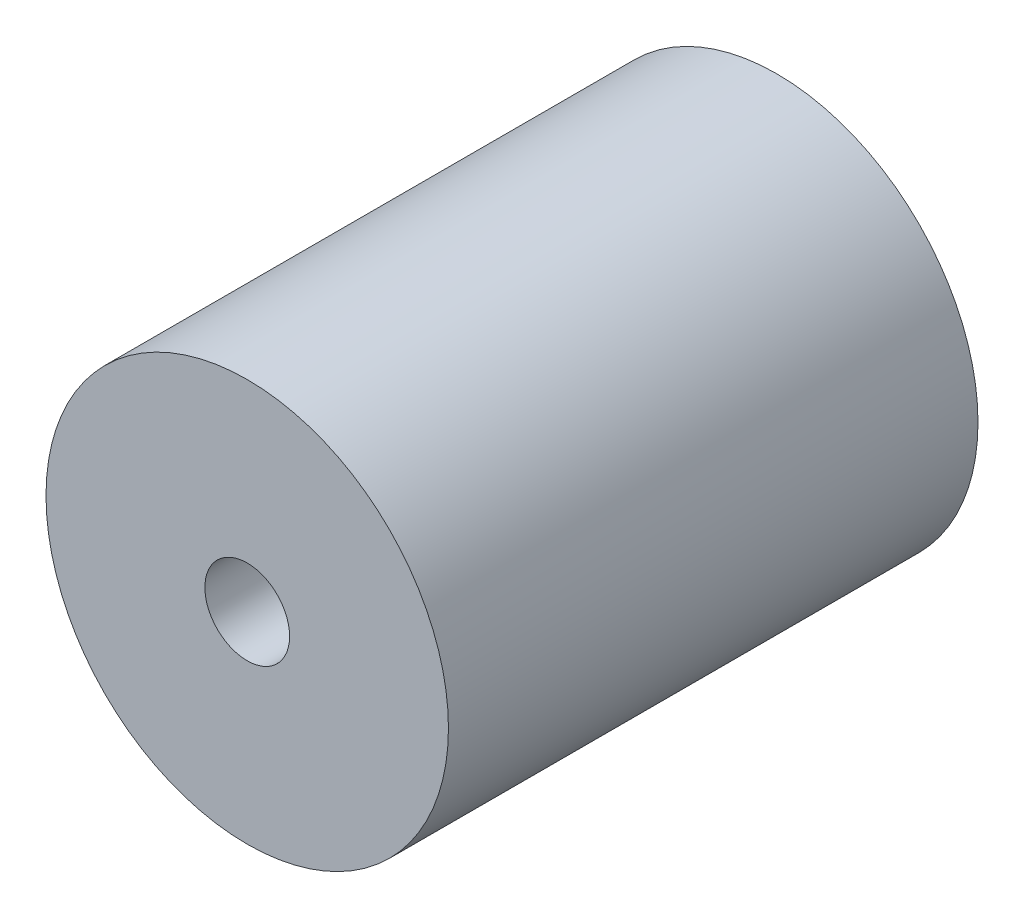
SolidWorks part; units mm, degrees
ref_plane "Front Plane" through (0, 0, 0) normal (0, 0, 1) x (1, 0, 0)
ref_plane "Top Plane" through (0, 0, 0) normal (0, 1, 0) x (1, 0, 0)
ref_plane "Right Plane" through (0, 0, 0) normal (1, 0, 0) x (0, 0, -1)
sketch "Sketch1" plane through (0, 0, 0) normal (0, 0, 1) x (1, 0, 0)
  circle A0 centre (0, 0) radius 9.5
  circle A1 centre (0, 0) radius 2
  dimension "D1" = 19
  dimension "D2" = 4
extrude "Boss-Extrude1" add sketch "Sketch1" along normal blind 25
